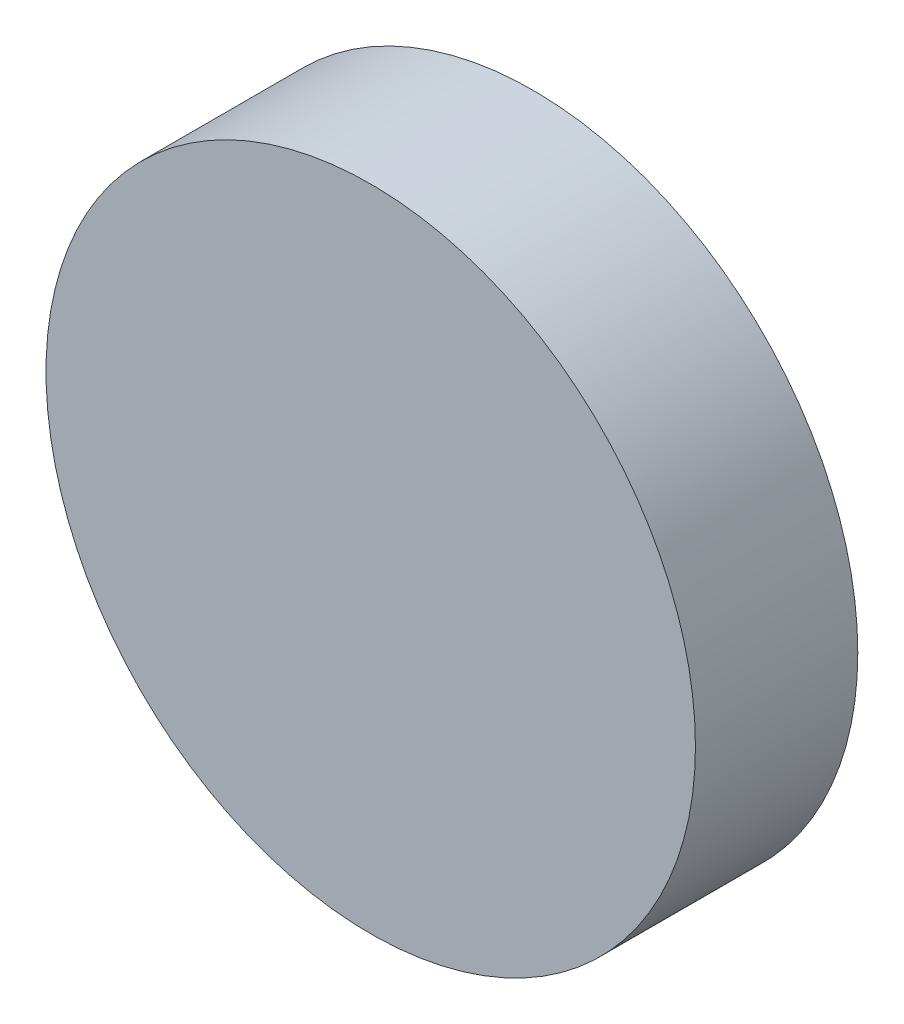
SolidWorks part; units mm, degrees
ref_plane "前视基准面" through (0, 0, 0) normal (0, 0, 1) x (1, 0, 0)
ref_plane "上视基准面" through (0, 0, 0) normal (0, 1, 0) x (1, 0, 0)
ref_plane "右视基准面" through (0, 0, 0) normal (1, 0, 0) x (0, 0, -1)
sketch "草图1" plane through (0, 0, 0) normal (0, 0, 1) x (1, 0, 0)
  circle A0 centre (0, 0) radius 50
  dimension "D1" = 100
extrude "凸台-拉伸1" add sketch "草图1" along normal blind 25
